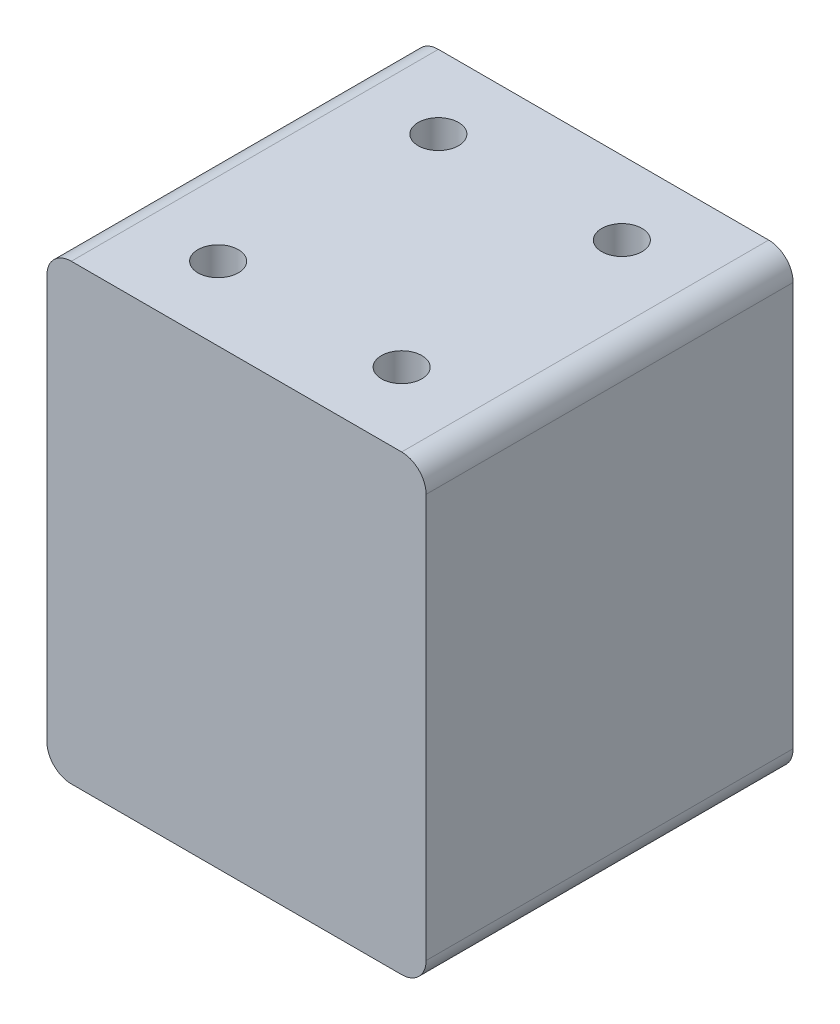
SolidWorks part; units mm, degrees
material "1.4000 (X6Cr13)"
ref_plane "前视基准面" through (0, 0, 0) normal (0, 0, 1) x (1, 0, 0)
ref_plane "上视基准面" through (0, 0, 0) normal (0, 1, 0) x (1, 0, 0)
ref_plane "右视基准面" through (0, 0, 0) normal (1, 0, 0) x (0, 0, -1)
sketch "草图1" plane through (0, 0, 0) normal (0, 0, 1) x (1, 0, 0)
  line L1 (-15.5, 18.5) -> (15.5, 18.5)
  line L2 (-15.5, 18.5) -> (-15.5, -18.5)
  line L3 (-15.5, -18.5) -> (15.5, -18.5)
  line L4 (15.5, 18.5) -> (15.5, -18.5)
  line L5 (-15.5, 18.5) -> (15.5, -18.5) construction
  line L6 (-15.5, -18.5) -> (15.5, 18.5) construction
  point P0 (0, 0)
  dimension "D1" = 31
  dimension "D2" = 37
extrude "凸台-拉伸1" add sketch "草图1" along normal blind 30
sketch "草图2" plane through (0, 18.5, 0) normal (0, 1, 0) x (1, 0, 0)
  line L2 (15.5, 0) -> (-15.5, 0) construction
  line L3 (-7.5, -6) -> (7.5, -6) construction
  line L4 (-7.5, -6) -> (-7.5, -24) construction
  line L5 (-7.5, -24) -> (7.5, -24) construction
  line L6 (7.5, -6) -> (7.5, -24) construction
  line L7 (-7.5, -6) -> (7.5, -24) construction
  line L8 (-7.5, -24) -> (7.5, -6) construction
  line L10 (15.5, -30) -> (15.5, 0) construction
  point P4 (0, -15)
  dimension "D1" = 15
  dimension "D2" = 18
  dimension "D3" = 6
  dimension "D4" = 8
hole_wizard "M4 螺纹孔1" positions "草图3" profile "草图4" tap size "M4" standard "GB"
sketch "草图3" plane through (0, 18.5, 0) normal (0, 1, 0) x (1, 0, 0)
  point P0 (-7.5, -6)
  point P3 (7.5, -6)
  point P6 (7.5, -24)
  point P9 (-7.5, -24)
sketch "草图4" plane through (-7.5, 18.5, 6) normal (1, 0, 0) x (0, 0, 1)
  line L0 (0, 0) -> (0, 9.9914)
  line L1 (0, 9.9914) -> (1.65, 9)
  line L2 (1.65, 9) -> (1.65, 0)
  line L5 (1.65, 0) -> (0, 0)
  line L10 (0, 9.9914) -> (-1.65, 9) construction
  line L11 (0, -6.35) -> (0, 107.95) construction
  dimension "螺纹孔钻头直径" = 3.3
  dimension "螺纹孔钻头深度" = 9
  dimension "导头角度" = 118
cosmetic thread "孔螺蚊线1" parameters "D1"=7, "D2"=4
cosmetic thread "孔螺蚊线2" parameters "D1"=7, "D2"=4
cosmetic thread "孔螺蚊线3" parameters "D1"=7, "D2"=4
cosmetic thread "孔螺蚊线4" parameters "D1"=7, "D2"=4
mirror "镜向1" about plane through (0, 0, 0) normal (0, 1, 0) of "M4 螺纹孔1"
cosmetic thread "孔螺蚊线5" parameters "D1"=7, "D2"=4
cosmetic thread "孔螺蚊线6" parameters "D1"=7, "D2"=4
cosmetic thread "孔螺蚊线7" parameters "D1"=7, "D2"=4
cosmetic thread "孔螺蚊线8" parameters "D1"=7, "D2"=4
sketch "草图5" plane through (-15.5, 0, 0) normal (-1, 0, 0) x (0, 0, 1)
  line L0 (30, 18.5) -> (0, 18.5) construction
  line L1 (11, 12.5) -> (19, 12.5) construction
  line L2 (11, 12.5) -> (11, -12.5) construction
  line L3 (11, -12.5) -> (19, -12.5) construction
  line L4 (19, 12.5) -> (19, -12.5) construction
  line L5 (11, 12.5) -> (19, -12.5) construction
  line L6 (11, -12.5) -> (19, 12.5) construction
  point P0 (15, 0)
  dimension "D1" = 8
  dimension "D2" = 25
  dimension "D3" = 11
  dimension "D4" = 6
hole_wizard "M4 螺纹孔2" positions "草图6" profile "草图7" tap size "M4" standard "GB"
sketch "草图6" plane through (-15.5, 0, 0) normal (-1, 0, 0) x (0, 0, 1)
  point P0 (11, 12.5)
  point P3 (19, 12.5)
  point P6 (19, -12.5)
  point P9 (11, -12.5)
sketch "草图7" plane through (-15.5, 12.5, 11) normal (0, 1, 0) x (0, 0, 1)
  line L0 (0, 0) -> (0, 10.9914)
  line L1 (0, 10.9914) -> (1.65, 10)
  line L2 (1.65, 10) -> (1.65, 0)
  line L5 (1.65, 0) -> (0, 0)
  line L10 (0, 10.9914) -> (-1.65, 10) construction
  line L11 (0, -6.35) -> (0, 107.95) construction
  dimension "螺纹孔钻头直径" = 3.3
  dimension "螺纹孔钻头深度" = 10
  dimension "导头角度" = 118
cosmetic thread "孔螺蚊线9" parameters "D1"=8, "D2"=4
cosmetic thread "孔螺蚊线10" parameters "D1"=8, "D2"=4
cosmetic thread "孔螺蚊线11" parameters "D1"=8, "D2"=4
cosmetic thread "孔螺蚊线12" parameters "D1"=8, "D2"=4
sketch "草图8" plane through (0, 0, 0) normal (0, 0, -1) x (-1, 0, 0)
  circle A0 centre (0, 0) radius 9.5
  dimension "D1" = 19
extrude "切除-拉伸1" cut sketch "草图8" against normal blind 9.7
sketch "草图9" plane through (0, 0, 9.7) normal (0, 0, -1) x (-1, 0, 0)
  circle A0 centre (0, 0) radius 8.65
  dimension "D1" = 17.3
extrude "切除-拉伸2" cut sketch "草图9" against normal blind 3.3
fillet "圆角1" radius 2 4 edges at (15.5, -18.5, 15) (-15.5, -18.5, 15) (-15.5, 18.5, 15) (15.5, 18.5, 15)
chamfer "倒角1" distance 1 angle 45 1 edges at (-9.5, 0, 0)
